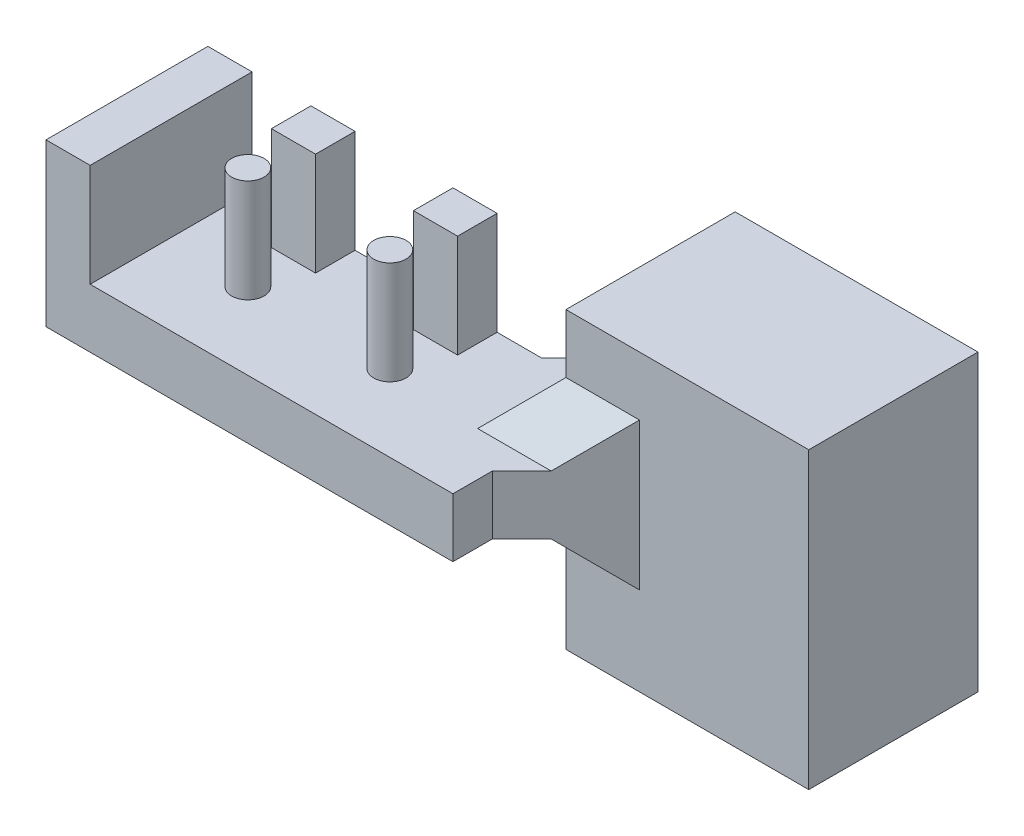
SolidWorks part; units mm, degrees
ref_plane "Front Plane" through (0, 0, 0) normal (0, 0, 1) x (1, 0, 0)
ref_plane "Top Plane" through (0, 0, 0) normal (0, 1, 0) x (1, 0, 0)
ref_plane "Right Plane" through (0, 0, 0) normal (1, 0, 0) x (0, 0, -1)
sketch "Sketch1" plane through (0, 0, 0) normal (0, 1, 0) x (1, 0, 0)
  line L1 (0, 0) -> (16.5, 0)
  line L2 (0, 0) -> (0, 11.5)
  line L3 (0, 11.5) -> (16.5, 11.5)
  line L4 (16.5, 0) -> (16.5, 11.5)
  line L5 (3, 3) -> (13.5, 3)
  line L6 (3, 3) -> (3, 8.5)
  line L7 (3, 8.5) -> (13.5, 8.5)
  line L8 (13.5, 3) -> (13.5, 8.5)
  point P9 (3, 5.75)
  point P10 (0, 5.75)
  point P11 (8.25, 3)
  point P12 (8.25, 0)
  dimension "D1" = 10.5
  dimension "D2" = 5.5
  dimension "D3" = 3
  dimension "D4" = 3
extrude "Boss-Extrude1" add sketch "Sketch1" along normal blind 17
sketch "Sketch2" plane through (0, 0, -11.5) normal (0, 0, -1) x (-1, 0, 0)
  line L0 (-16.5, 17) -> (0, 17) construction
  circle A0 centre (-8.25, 10.5) radius 2.5
  point P2 (0, 0)
  point P5 (-8.25, 17)
  dimension "D1" = 5
  dimension "D2" = 6.5
extrude "Cut-Extrude1" cut sketch "Sketch2" against normal up to next
sketch "Sketch3" plane through (0, 17, 0) normal (0, 1, 0) x (1, 0, 0)
  line L1 (0, 11.5) -> (16.5, 11.5)
  line L2 (0, 11.5) -> (0, 0)
  line L3 (0, 0) -> (16.5, 0)
  line L4 (16.5, 11.5) -> (16.5, 0)
extrude "Boss-Extrude2" add sketch "Sketch3" along normal blind 3
sketch "Sketch4" plane through (0, 20, 0) normal (0, 1, 0) x (1, 0, 0)
  line L0 (16.5, 11.5) -> (0, 11.5) construction
  line L1 (-21.75, -7.676) -> (0, -7.676)
  line L2 (-21.75, -7.676) -> (-21.75, 0.324)
  line L3 (-21.75, 0.324) -> (0, 0.324)
  line L4 (0, -7.676) -> (0, 0.324)
  line L6 (0, 0) -> (16.5, 0) construction
  line L7 (0, 11.5) -> (0, 0) construction
  line L9 (-21.75, 0.324) -> (0, 0.324)
  line L10 (-21.75, 0.324) -> (-21.75, 3.324)
  line L11 (-21.75, 3.324) -> (0, 3.324)
  line L12 (0, 0.324) -> (0, 3.324)
  point P8 (8.25, 0)
  line M5 (0, 11.5) -> (0, 0)
  dimension "D1" = 11.176
  dimension "D2" = 30
  dimension "D3" = 8
  dimension "D4" = 3
extrude "Boss-Extrude3" add sketch "Sketch4" along normal blind 4 from offset 11 contours L11 L10 L3 M5 | L1 L4 L3 L2 M5 offset against normal yes
chamfer "Chamfer1" distance 5 angle 45 2 edges at (0, 11, 0) (0, 11, -3.324)
chamfer "Chamfer2" distance 3 angle 45 4 edges at (0, 9, -4.162) (2.5, 9, 0) (2.5, 13, 0) (0, 13, -4.162)
sketch "Sketch5" plane through (0, 13, 0) normal (0, 1, 0) x (1, 0, 0)
  line L1 (-20.65, 3.324) -> (-17.65, 3.324)
  line L2 (-20.65, 3.324) -> (-20.65, 0.64)
  line L3 (-20.65, 0.64) -> (-17.65, 0.64)
  line L4 (-17.65, 3.324) -> (-17.65, 0.64)
  line L6 (-11, 3.324) -> (-8, 3.324)
  line L7 (-11, 3.324) -> (-11, 0.64)
  line L8 (-11, 0.64) -> (-8, 0.64)
  line L9 (-8, 3.324) -> (-8, 0.64)
  line L10 (-21.4804, -11.36) -> (-3.4221, -11.36) construction
  line L11 (16.5, 11.5) -> (0, 11.5) construction
  line L12 (-3, -3) -> (-3, 5.324) construction
  line L13 (-21.75, 3.324) -> (-5, 3.324) construction
  circle A0 centre (-19.15, -2.46) radius 1.1
  circle A1 centre (-9.5, -2.46) radius 1.1
  point P15 (-19.15, 0.64)
  point P16 (-9.5, 0.64)
  dimension "D1" = 2.2
  dimension "D2" = 3
  dimension "D3" = 3.1
  dimension "D4" = 3.1
  dimension "D5" = 3
  dimension "D6" = 5
  dimension "D7" = 9.65
  dimension "D8" = 12
  dimension "D9" = 22.86
extrude "Boss-Extrude4" add sketch "Sketch5" along normal blind 7
sketch "Sketch6" plane through (0, 0, 7.676) normal (0, 0, 1) x (1, 0, 0)
  line L0 (-21.75, 13) -> (-24.65, 13)
  line L1 (-24.65, 13) -> (-24.65, 20)
  line L2 (-24.65, 20) -> (-27.65, 20)
  line L3 (-27.65, 20) -> (-27.65, 9)
  line L4 (-27.65, 9) -> (-21.75, 9)
  line L5 (-18.05, 20) -> (-20.25, 20) construction
  line L6 (-18.05, 20) -> (-20.25, 20) construction
  line L11 (-21.75, 9) -> (0, 9)
  line L12 (0, 9) -> (0, 13)
  line L13 (0, 13) -> (-21.75, 13)
  line L14 (-21.75, 13) -> (-21.75, 9)
  line L18 (-21.75, 13) -> (-21.75, 9)
  point P4 (0, 0)
  point P11 (-19.15, 20)
  point P12 (0, 0)
  dimension "D1" = 5.5
  dimension "D2" = 3
  dimension "D3" = 0
extrude "Boss-Extrude5" add sketch "Sketch6" against normal up to surface (11 mm away) up to face at (-14.0083, 14.6667, -3.324)
sketch "Sketch7" plane through (0, 0, -11.5) normal (0, 0, -1) x (-1, 0, 0)
  line L0 (-3, 17) -> (-13.5, 17) construction
  line L1 (-13.5, 17) -> (-3, 17)
  line L2 (-13.5, 17) -> (-13.5, 15.5)
  line L3 (-13.5, 15.5) -> (-3, 15.5)
  line L4 (-3, 17) -> (-3, 15.5)
  line L5 (-13.5, 17) -> (-13.5, 0) construction
  line L6 (-3, 17) -> (-3, 0) construction
  dimension "D1" = 1.5
extrude "Cut-Extrude2" cut sketch "Sketch7" against normal up to next
